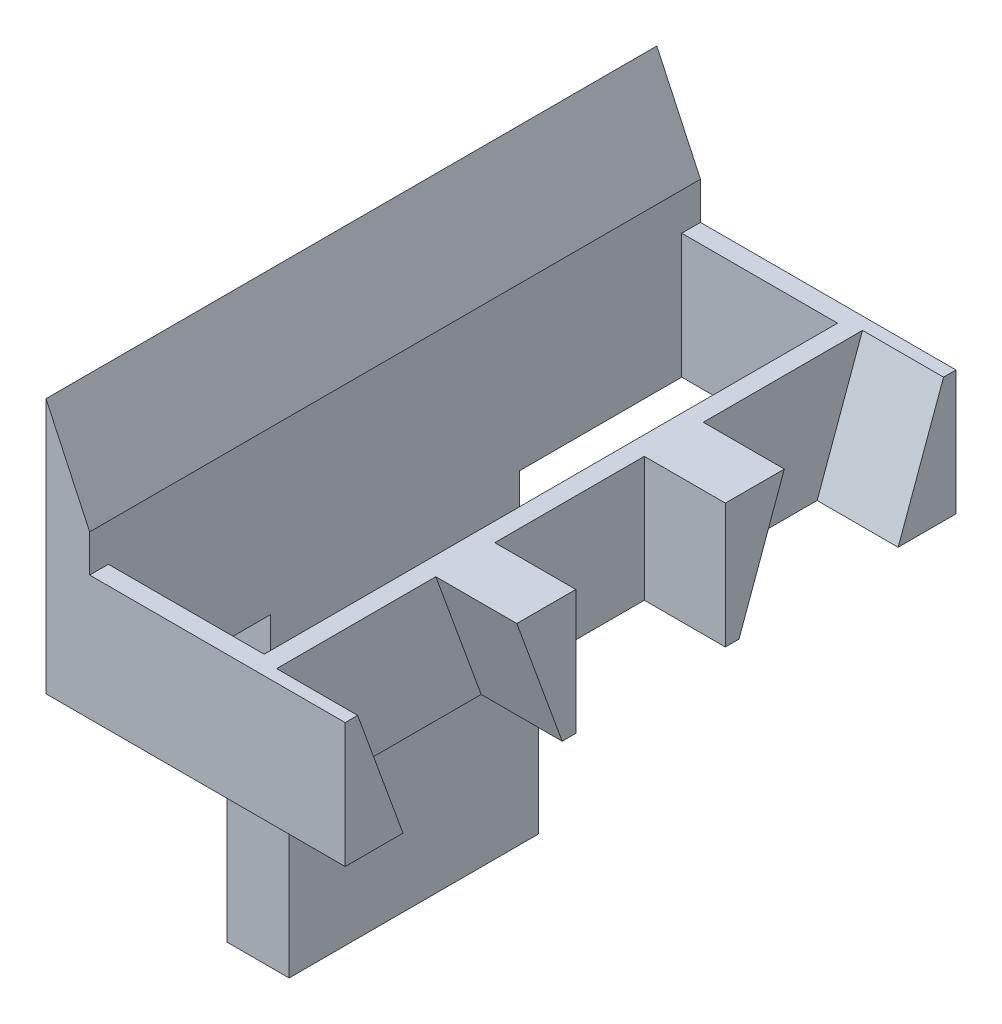
SolidWorks part; units mm, degrees
material "ABS"
ref_plane "Front Plane" through (0, 0, 0) normal (0, 0, 1) x (1, 0, 0)
ref_plane "Top Plane" through (0, 0, 0) normal (0, 1, 0) x (1, 0, 0)
ref_plane "Right Plane" through (0, 0, 0) normal (1, 0, 0) x (0, 0, -1)
sketch "Croquis1" plane through (0, 0, 0) normal (0, 0, 1) x (1, 0, 0)
  line L0 (-3.5, 49.5) -> (-3.5, 0)
  line L1 (-3.5, 0) -> (0, 0)
  line L2 (0, 0) -> (0, 41.9942)
  line L3 (0, 41.9942) -> (-3.5, 49.5)
  dimension "D1" = 3.5
  dimension "D2" = 49.5
  dimension "D3" = 25
extrude "Saliente-Extruir1" add sketch "Croquis1" along normal blind 49
sketch "Croquis2" plane through (0, 0, 0) normal (1, 0, 0) x (0, 0, -1)
  line L0 (-49, 0) -> (0, 0)
  line L2 (-49, 0) -> (-49, 28.9942)
  line L3 (-49, 28.9942) -> (-34.5, 28.9942)
  line L4 (-34.5, 4.5) -> (-34.5, 28.9942)
  line L6 (0, 0) -> (0, 28.9942)
  line L7 (0, 28.9942) -> (-14.5, 28.9942)
  line L8 (-14.5, 4.5) -> (-14.5, 28.9942)
  line L11 (-34.5, 4.5) -> (-14.5, 4.5)
  line L12 (-49, 41.9942) -> (0, 41.9942) construction
  point P14 (-24.5, 35.4942)
  dimension "D1" = 13
  dimension "D2" = 20
  dimension "D3" = 4.5
  dimension "D4" = 13
extrude "Cortar-Extruir1" cut sketch "Croquis2" against normal through all
sketch "Croquis4" plane through (0, 28.9942, 0) normal (0, -1, 0) x (1, 0, 0)
  line L0 (0, 49) -> (20.5, 49)
  line L2 (20.5, 0) -> (0, 0)
  line L6 (12.5, 47.5) -> (12.5, 1.5)
  line L8 (12.5, 47.5) -> (0, 47.5)
  line L9 (0, 34.5) -> (0, 49) construction
  line L10 (0, 47.5) -> (0, 49)
  line L11 (12.5, 1.5) -> (0, 1.5)
  line L12 (0, 0) -> (0, 14.5) construction
  line L13 (0, 1.5) -> (0, 0)
  line L22 (20.5, 49) -> (20.5, 0)
  dimension "D1" = 46
  dimension "D2" = 8
  dimension "D3" = 12.5
extrude "Saliente-Extruir3" add sketch "Croquis4" against normal blind 10
sketch "Croquis8" plane through (20.5, 0, 0) normal (1, 0, 0) x (0, 0, -1)
  line L0 (-30.5, 38.9942) -> (-18.5, 38.9942)
  line L1 (0, 38.9942) -> (-49, 38.9942) construction
  line L2 (0, 28.9942) -> (-49, 28.9942) construction
  line L4 (-18.5, 28.9942) -> (-18.5, 38.9942)
  line L10 (-30.5, 28.9942) -> (-30.5, 38.9942)
  line L11 (-30.5, 28.9942) -> (-18.5, 28.9942)
  line L12 (-48, 38.9942) -> (-44.3603, 28.9942)
  line L13 (-49, 38.9942) -> (-49, 28.9942) construction
  line L15 (-35.2299, 38.9942) -> (-31.5902, 28.9942)
  line L16 (-31.5902, 28.9942) -> (-44.3603, 28.9942)
  line L17 (-48, 38.9942) -> (-35.2299, 38.9942)
  line L18 (-17.4098, 28.9942) -> (-4.6397, 28.9942)
  line L19 (-1, 38.9942) -> (-4.6397, 28.9942)
  line L20 (-13.7701, 38.9942) -> (-17.4098, 28.9942)
  line L21 (-1, 38.9942) -> (-13.7701, 38.9942)
  dimension "D1" = 20
  dimension "D2" = 1
extrude "Cortar-Extruir2" cut sketch "Croquis8" against normal blind 6.5
sketch "Croquis9" plane through (0, 0, 0) normal (1, 0, 0) x (0, 0, -1)
  line L0 (-14.5, 28.9942) -> (-14.5, 4.5) construction
  line L1 (-34.5, 4.5) -> (-14.5, 4.5)
  line L2 (-34.5, 4.5) -> (-34.5, 16.5)
  line L3 (-34.5, 16.5) -> (-14.5, 16.5)
  line L4 (-14.5, 4.5) -> (-14.5, 16.5)
  dimension "D1" = 12
extrude "Saliente-Extruir4" add sketch "Croquis9" along normal blind 1.5
